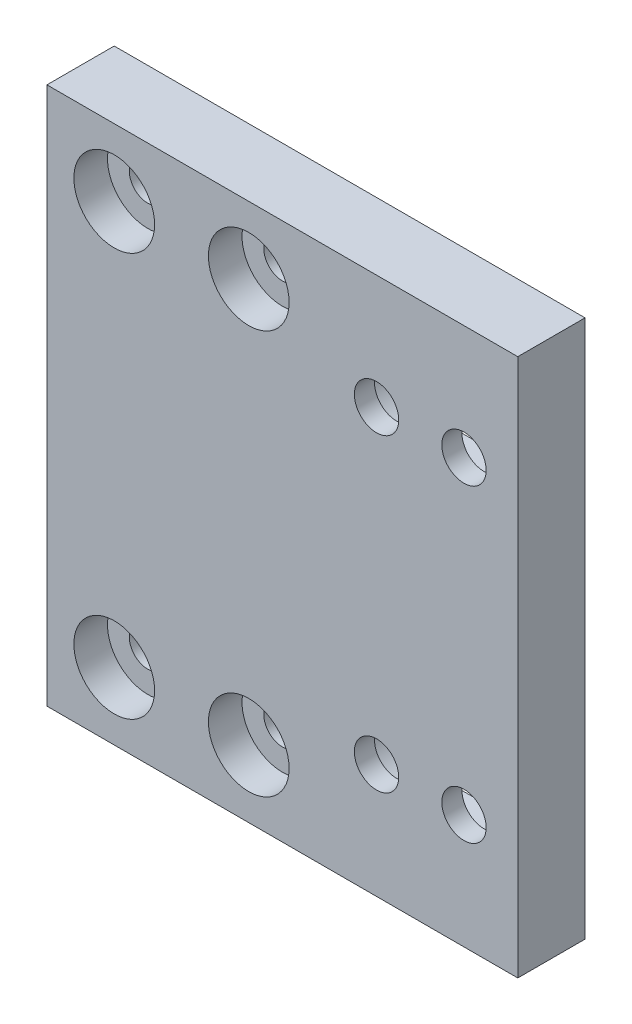
SolidWorks part; units mm, degrees
ref_plane "Plan de face" through (0, 0, 0) normal (0, 0, 1) x (1, 0, 0)
ref_plane "Plan de dessus" through (0, 0, 0) normal (0, 1, 0) x (1, 0, 0)
ref_plane "Plan de droite" through (0, 0, 0) normal (1, 0, 0) x (0, 0, -1)
sketch "Esquisse1" plane through (0, 0, 0) normal (0, 0, 1) x (1, 0, 0)
  line L0 (0.8219, 24.138) -> (0.8219, -21.862) construction
  line L1 (-61.1781, 41.138) -> (8.8219, 41.138)
  line L2 (-61.1781, 41.138) -> (-61.1781, -38.862)
  line L3 (-61.1781, -38.862) -> (8.8219, -38.862)
  line L4 (8.8219, 41.138) -> (8.8219, -38.862)
  circle A0 centre (0.8219, 24.138) radius 3.3
  circle A1 centre (-12.1781, 24.138) radius 3.3
  circle A2 centre (-12.1781, -21.862) radius 3.3
  circle A3 centre (0.8219, -21.862) radius 3.3
  circle A4 centre (-51.1781, 31.138) radius 2.75
  circle A5 centre (-31.1781, 31.138) radius 2.75
  circle A6 centre (-31.1781, -28.862) radius 2.75
  circle A7 centre (-51.1781, -28.862) radius 2.75
  point P12 (0.8219, 1.138)
  point P13 (8.8219, 1.138)
  dimension "D1" = 6.6
  dimension "D7" = 5.5
  dimension "D2" = 8
  dimension "D3" = 13
  dimension "D4" = 46
  dimension "D5" = 80
  dimension "D6" = 70
  dimension "D8" = 10
  dimension "D9" = 10
  dimension "D10" = 20
  dimension "D11" = 10
extrude "Boss.-Extru.1" add sketch "Esquisse1" along normal blind 10
sketch "Esquisse2" plane through (0, 0, 10) normal (0, 0, 1) x (1, 0, 0)
  circle A0 centre (-51.1781, 31.138) radius 6
  circle A1 centre (-31.1781, 31.138) radius 6
  circle A2 centre (-31.1781, -28.862) radius 6
  circle A3 centre (-51.1781, -28.862) radius 6
  dimension "D1" = 12
extrude "Enlèv. mat.-Extru.1" cut sketch "Esquisse2" against normal blind 5
sketch "Esquisse3" plane through (0, 0, 0) normal (0, 0, -1) x (-1, 0, 0)
  line L0 (-0.8219, 31.138) -> (12.1781, 31.138)
  line L1 (-0.8219, 17.138) -> (12.1781, 17.138)
  line L2 (-0.8219, -21.862) -> (12.1781, -21.862) construction
  line L3 (-0.8219, -14.862) -> (12.1781, -14.862)
  line L4 (-0.8219, -28.862) -> (12.1781, -28.862)
  arc A4 (-0.8219, 31.138) -> (-0.8219, 17.138) centre (-0.8219, 24.138) ccw
  arc A5 (12.1781, 31.138) -> (12.1781, 17.138) centre (12.1781, 24.138) cw
  arc A6 (-0.8219, -14.862) -> (-0.8219, -28.862) centre (-0.8219, -21.862) ccw
  arc A7 (12.1781, -28.862) -> (12.1781, -14.862) centre (12.1781, -21.862) ccw
  point P6 (5.6781, -21.862)
  dimension "D1" = 7
  dimension "D2" = 7
extrude "Enlèv. mat.-Extru.3" cut sketch "Esquisse3" against normal blind 7
